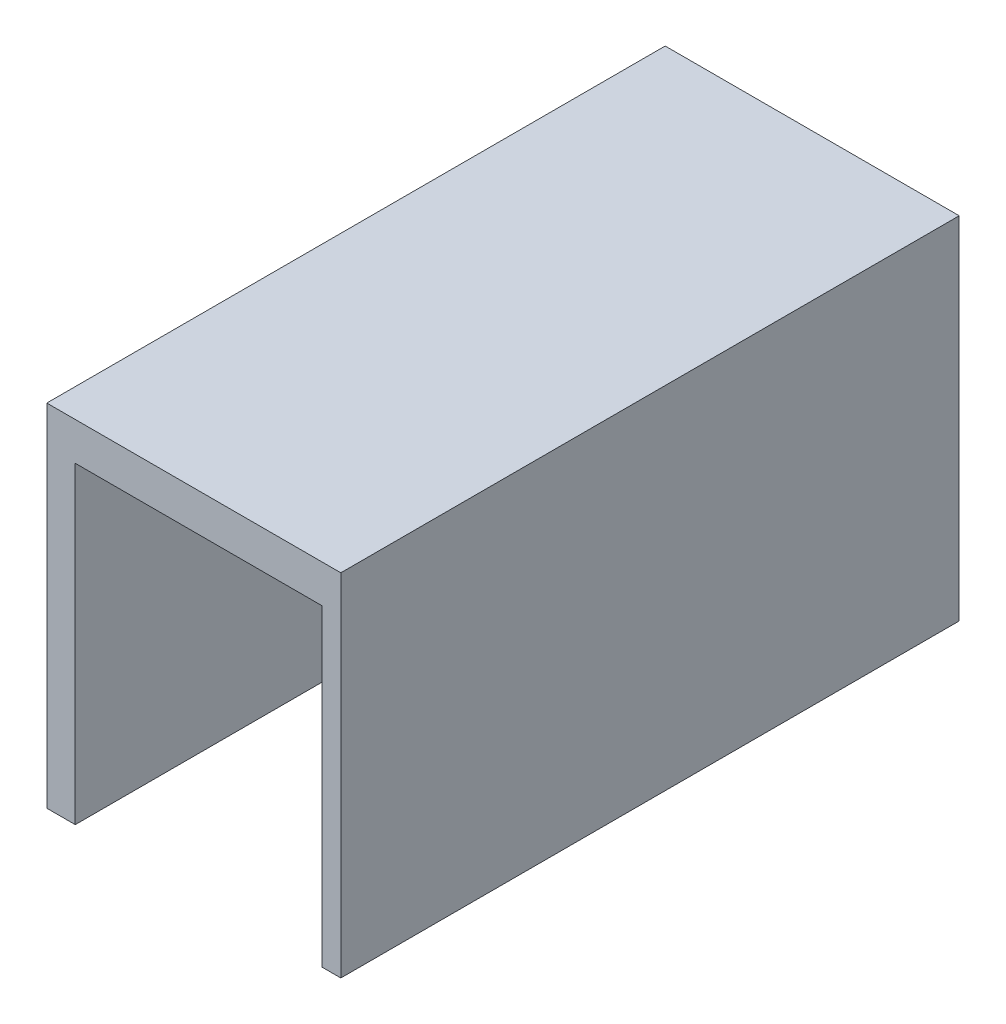
SolidWorks part; units mm, degrees
material "PLA"
ref_plane "Front Plane" through (0, 0, 0) normal (0, 0, 1) x (1, 0, 0)
ref_plane "Top Plane" through (0, 0, 0) normal (0, 1, 0) x (1, 0, 0)
ref_plane "Right Plane" through (0, 0, 0) normal (1, 0, 0) x (0, 0, -1)
sketch "Sketch2" plane through (0, 0, 0) normal (0, 0, 1) x (1, 0, 0)
  line L0 (-13, -16.5) -> (-15, -16.5)
  line L1 (13, -16.5) -> (-13, -16.5) construction
  line L2 (13, -16.5) -> (13, 16.5)
  line L3 (13, 16.5) -> (-13, 16.5)
  line L4 (-13, -16.5) -> (-13, 16.5)
  line L5 (13, -16.5) -> (-13, 16.5) construction
  line L6 (13, 16.5) -> (-13, -16.5) construction
  line L7 (-15, -16.5) -> (-15, 20.5)
  line L8 (-15, 20.5) -> (15, 20.5)
  line L9 (15, 20.5) -> (15, -16.5)
  line L10 (15, -16.5) -> (13, -16.5)
  point P0 (0, 0)
  dimension "D1" = 37
  dimension "D2" = 26
  dimension "D3" = 33
  dimension "D4" = 2
  dimension "D5" = 2
extrude "Front Profile" add sketch "Sketch2" along normal blind 65.2
sketch "Sketch3" plane through (-15, 0, 0) normal (-1, 0, 0) x (0, 0, 1)
  line L0 (0, 20.5) -> (65.2, -16.5) construction
  line L1 (65.2, 20.5) -> (0, -16.5) construction
  line L3 (64.53, -15.83) -> (0.67, -15.83)
  line L4 (64.53, -15.83) -> (64.53, 19.83)
  line L5 (64.53, 19.83) -> (0.67, 19.83)
  line L6 (0.67, -15.83) -> (0.67, 19.83)
  line L7 (64.53, -15.83) -> (0.67, 19.83) construction
  line L8 (64.53, 19.83) -> (0.67, -15.83) construction
  line L9 (65.2, -16.5) -> (0, -16.5)
  line L10 (65.2, -16.5) -> (65.2, 20.5)
  line L11 (65.2, 20.5) -> (0, 20.5)
  line L12 (0, -16.5) -> (0, 20.5)
  line L13 (65.2, -16.5) -> (0, 20.5) construction
  line L14 (65.2, 20.5) -> (0, -16.5) construction
  point P8 (32.6, 2)
  point P13 (32.6, 2)
  dimension "D1" = 35.66
  dimension "D2" = 63.86
extrude "Housing SnapOn" add sketch "Sketch3" along normal blind 1
